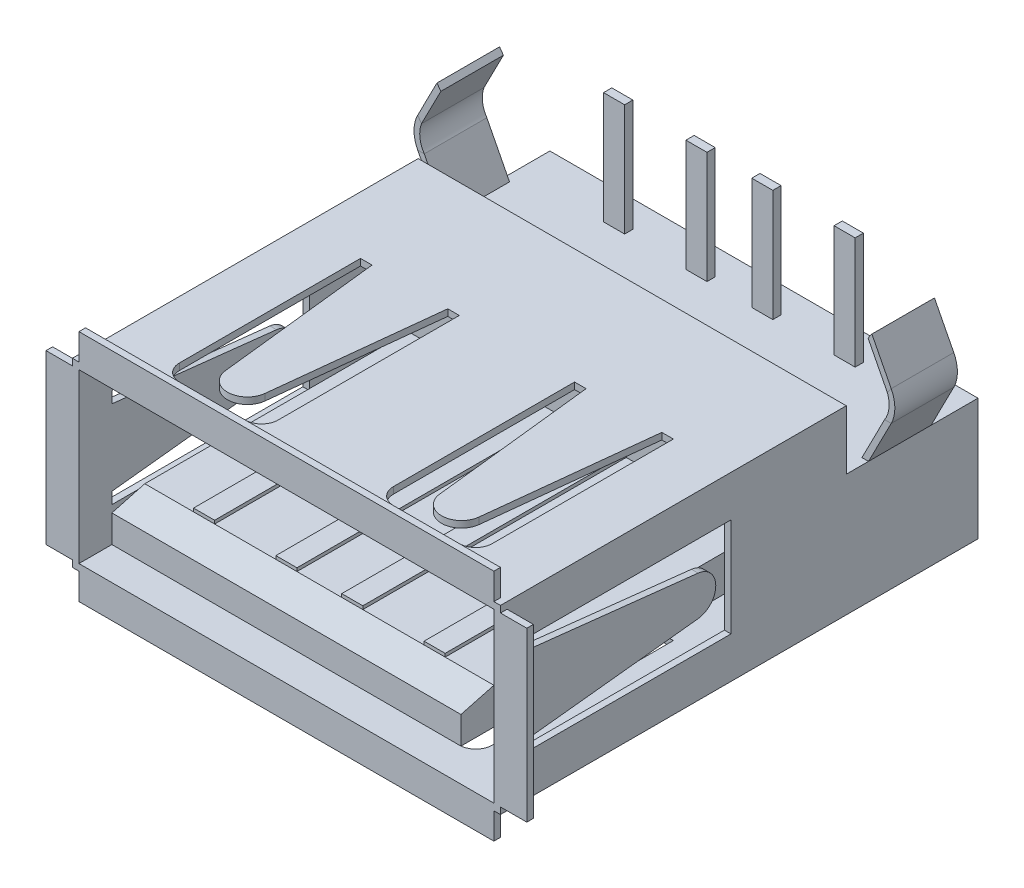
SolidWorks part; units mm, degrees
ref_plane "前视基准面" through (0, 0, 0) normal (0, 0, 1) x (1, 0, 0)
ref_plane "上视基准面" through (0, 0, 0) normal (0, 1, 0) x (1, 0, 0)
ref_plane "右视基准面" through (0, 0, 0) normal (1, 0, 0) x (0, 0, -1)
sketch "草图1" plane through (0, 0, 0) normal (0, 0, 1) x (1, 0, 0)
  line L1 (6.5, -2.75) -> (-6.5, -2.75)
  line L2 (6.5, -2.75) -> (6.5, 2.75)
  line L3 (6.5, 2.75) -> (-6.5, 2.75)
  line L4 (-6.5, -2.75) -> (-6.5, 2.75)
  line L5 (6.5, -2.75) -> (-6.5, 2.75) construction
  line L6 (6.5, 2.75) -> (-6.5, -2.75) construction
  point P0 (0, 0)
  dimension "D1" = 13
  dimension "D2" = 5.5
extrude "凸台-拉伸1" add sketch "草图1" along normal blind 14.5
sketch "草图2" plane through (0, 0, 14.5) normal (0, 0, 1) x (1, 0, 0)
  line L17 (6.3, 2.55) -> (-6.3, 2.55)
  line L18 (6.3, -2.55) -> (6.3, 2.55)
  line L19 (-6.3, -2.55) -> (6.3, -2.55)
  line L20 (-6.3, 2.55) -> (-6.3, -2.55)
  line L21 (6.3, 2.55) -> (-6.3, 2.55)
  line L22 (6.3, -2.55) -> (6.3, 2.55)
  line L23 (-6.3, -2.55) -> (6.3, -2.55)
  line L24 (-6.3, 2.55) -> (-6.3, -2.55)
  dimension "D2" = 0.2
extrude "切除-拉伸1" cut sketch "草图2" against normal blind 9
sketch "草图11" plane through (0, -2.75, 0) normal (0, -1, 0) x (1, 0, 0)
  line L0 (4.75, 7.5) -> (4.75, 13)
  line L1 (4.25, 13.5) -> (2.25, 13.5)
  line L2 (1.75, 13) -> (1.75, 7.5)
  line L3 (4.75, 7.5) -> (4.4, 7.5)
  line L4 (2.1, 7.5) -> (2.65, 12.5)
  line L5 (2.1, 7.5) -> (1.75, 7.5)
  line L6 (3.85, 12.5) -> (4.4, 7.5)
  line L7 (0, 0) -> (0, 15.6851) construction
  line L8 (3.25, 5.9079) -> (3.25, 13.4637) construction
  line L10 (6.5, 14.5) -> (6.5, 0) construction
  line L11 (-3.85, 12.5) -> (-4.4, 7.5)
  line L12 (-2.1, 7.5) -> (-1.75, 7.5)
  line L13 (-2.1, 7.5) -> (-2.65, 12.5)
  line L14 (-4.75, 7.5) -> (-4.4, 7.5)
  line L15 (-1.75, 13) -> (-1.75, 7.5)
  line L16 (-4.25, 13.5) -> (-2.25, 13.5)
  line L17 (-4.75, 7.5) -> (-4.75, 13)
  line L18 (-6.5, 14.5) -> (6.5, 14.5) construction
  arc A0 (1.75, 13) -> (2.25, 13.5) centre (2.25, 13) cw
  arc A1 (4.25, 13.5) -> (4.75, 13) centre (4.25, 13) cw
  arc A2 (2.65, 12.5) -> (3.85, 12.5) centre (3.25, 12.434) cw
  arc A3 (-2.65, 12.5) -> (-3.85, 12.5) centre (-3.25, 12.434) ccw
  arc A4 (-4.25, 13.5) -> (-4.75, 13) centre (-4.25, 13) ccw
  arc A5 (-1.75, 13) -> (-2.25, 13.5) centre (-2.25, 13) ccw
  point P17 (1.75, 13.5)
  point P20 (4.75, 13.5)
  point P35 (-4.75, 13.5)
  point P36 (-1.75, 13.5)
  dimension "D6" = 0.5
  dimension "D1" = 2.3
  dimension "D2" = 3
  dimension "D3" = 6
  dimension "D4" = 1.2
  dimension "D5" = 5
  dimension "D7" = 1
extrude "切除-拉伸3" cut sketch "草图11" against normal through all
sketch "草图12" plane through (6.5, 0, 0) normal (1, 0, 0) x (0, 0, -1)
  line L0 (-13.5, -1.5) -> (-7.5, -1.5)
  line L1 (-7.5, -1.5) -> (-7.5, 1.5)
  line L2 (-7.5, 1.5) -> (-13.5, 1.5)
  line L3 (-13.5, 1.5) -> (-13.5, 1.15)
  line L4 (-13.5, 1.15) -> (-8.5, 0.6)
  line L6 (-8.5, -0.6) -> (-13.5, -1.15)
  line L7 (-13.5, -1.15) -> (-13.5, -1.5)
  line L8 (0, 0) -> (-16.0107, 0) construction
  line L9 (-14.5, -2.75) -> (-14.5, 2.75) construction
  arc A0 (-8.5, -0.6) -> (-8.5, 0.6) centre (-8.566, 0) ccw
  dimension "D1" = 1
  dimension "D2" = 6
  dimension "D3" = 5
  dimension "D4" = 3
  dimension "D5" = 2.3
  dimension "D6" = 1.2
extrude "切除-拉伸4" cut sketch "草图12" against normal through all
sketch "草图5" plane through (0, 0, 5.5) normal (0, 0, 1) x (1, 0, 0)
  line L0 (0, -1.4303) -> (0, 3.5568) construction
  line L1 (5.3, -1.55) -> (-5.3, -1.55)
  line L2 (5.3, -1.55) -> (5.3, -0.45)
  line L3 (5.3, -0.45) -> (-5.3, -0.45)
  line L4 (-5.3, -1.55) -> (-5.3, -0.45)
  line L5 (5.3, -1.55) -> (-5.3, -0.45) construction
  line L6 (5.3, -0.45) -> (-5.3, -1.55) construction
  line L7 (-6.3, 2.55) -> (-6.3, -2.55) construction
  line L8 (-6.3, -2.55) -> (6.3, -2.55) construction
  point P0 (0, -1)
  dimension "D1" = 1.1
  dimension "D2" = 1
  dimension "D3" = 1
extrude "凸台-拉伸3" add sketch "草图5" along normal up to surface (9 mm away) up to face at (0, 0, 14.5)
chamfer "倒角1" distance 1 angle 15 1 edges at (0, -0.45, 14.5)
sketch "草图3" plane through (0, 2.75, 0) normal (0, 1, 0) x (1, 0, 0)
  line L0 (-6.5, -14.5) -> (-6.5, 0) construction
  line L1 (6.5, 0) -> (-6.5, 0)
  line L2 (6.5, 0) -> (6.5, -4)
  line L3 (6.5, -4) -> (-6.5, -4)
  line L4 (-6.5, 0) -> (-6.5, -4)
  dimension "D1" = 4
extrude "切除-拉伸2" cut sketch "草图3" against normal blind 1.8
sketch "草图9" plane through (0, 0.95, 2.45) normal (0, -1, 0) x (-1, 0, 0)
  line L0 (0, 2.45) -> (0, -1.3538) construction
  line L1 (-3.82, 1.65) -> (-3.18, 1.65)
  line L2 (-3.82, 1.65) -> (-3.82, 1.4)
  line L3 (-3.82, 1.4) -> (-3.18, 1.4)
  line L4 (-3.18, 1.65) -> (-3.18, 1.4)
  line L6 (-6.5, 2.45) -> (6.5, 2.45) construction
  line L7 (0.68, 1.4) -> (0.68, 1.65)
  line L8 (-1.32, 1.4) -> (-0.68, 1.4)
  line L9 (-1.32, 1.4) -> (-1.32, 1.65)
  line L10 (-1.32, 1.65) -> (-0.68, 1.65)
  line L11 (-0.68, 1.4) -> (-0.68, 1.65)
  line L12 (1.32, 1.65) -> (0.68, 1.65)
  line L13 (1.32, 1.4) -> (1.32, 1.65)
  line L14 (1.32, 1.4) -> (0.68, 1.4)
  line L15 (3.18, 1.65) -> (3.18, 1.4)
  line L16 (3.82, 1.4) -> (3.18, 1.4)
  line L17 (3.82, 1.65) -> (3.82, 1.4)
  line L18 (3.82, 1.65) -> (3.18, 1.65)
  line L20 (-6.5, -1.55) -> (-6.5, 2.45) construction
  line L21 (-6.5, -0.875) -> (-6.3, -0.875) construction
  line L22 (-6.5, -0.875) -> (-6.5, 1.025) construction
  line L23 (-6.5, 1.025) -> (-6.3, 1.025) construction
  line L24 (-6.3, -0.875) -> (-6.3, 1.025) construction
  point P6 (-1, 1.65)
  point P10 (-3.5, 1.65)
  point P28 (-3.82, 1.525)
  point P29 (-6.3, 0.075)
  dimension "D1" = 0.64
  dimension "D2" = 0.25
  dimension "D3" = 3.5
  dimension "D4" = 1
  dimension "D5" = 0.8
  dimension "D6" = 0.2
  dimension "D7" = 1.9
  dimension "D8" = 1.45
extrude "凸台-拉伸5" add sketch "草图9" against normal blind 3.4
sketch "草图14" plane through (0, -0.45, 0) normal (0, 1, 0) x (1, 0, 0)
  line L1 (-3.82, -5.37) -> (-3.18, -5.37)
  line L2 (-3.82, -5.37) -> (-3.82, -13.5)
  line L3 (-3.82, -13.5) -> (-3.18, -13.5)
  line L4 (-3.18, -5.37) -> (-3.18, -13.5)
  line L5 (-1.32, -5.37) -> (-0.68, -5.37)
  line L6 (-1.32, -5.37) -> (-1.32, -13.5)
  line L7 (-1.32, -13.5) -> (-0.68, -13.5)
  line L8 (-0.68, -5.37) -> (-0.68, -13.5)
  line L9 (0.68, -5.37) -> (1.32, -5.37)
  line L10 (0.68, -5.37) -> (0.68, -13.5)
  line L11 (0.68, -13.5) -> (1.32, -13.5)
  line L12 (1.32, -5.37) -> (1.32, -13.5)
  line L13 (3.18, -5.37) -> (3.82, -5.37)
  line L14 (3.18, -5.37) -> (3.18, -13.5)
  line L15 (3.18, -13.5) -> (3.82, -13.5)
  line L16 (3.82, -5.37) -> (3.82, -13.5)
  line L19 (3.18, -1.05) -> (3.18, -0.8) construction
  line L20 (3.82, -0.8) -> (3.82, -1.05) construction
  line L21 (-5.3, -13.5) -> (5.3, -13.5) construction
extrude "凸台-拉伸6" add sketch "草图14" along normal blind 0.1
sketch "草图15" plane through (0, 0.95, 0) normal (0, 1, 0) x (1, 0, 0)
  line L0 (0, 0) -> (0, -3.8038) construction
  line L5 (-6.3, -3.325) -> (-6.3, -1.425)
  line L6 (-6.5, -1.425) -> (-6.3, -1.425)
  line L7 (-6.5, -3.325) -> (-6.5, -1.425)
  line L8 (-6.5, -3.325) -> (-6.3, -3.325)
sketch "草图16" plane through (0, 0, 0) normal (0, 0, -1) x (-1, 0, 0)
  line L0 (6.5, 0.95) -> (7.1896, 2.2933)
  line L1 (7.1896, 3.2067) -> (6.6027, 4.35)
  line L3 (6.5, 0.95) -> (-6.5, 0.95) construction
  line L5 (6.5, 2.75) -> (-6.5, 2.75) construction
  arc A0 (7.1896, 2.2933) -> (7.1896, 3.2067) centre (6.3, 2.75) ccw
  point P13 (7.4241, 2.75)
  point P14 (7.3, 2.75)
  dimension "D3" = 1
  dimension "D1" = 3.4
  dimension "D2" = 7.3
sweep "扫描1" add profiles "草图15" path "草图16"
mirror "镜向1" about plane through (0, 0, 0) normal (1, 0, 0) of "扫描1"
sketch "草图17" plane through (0, 0, 14.5) normal (0, 0, 1) x (1, 0, 0)
  line L0 (-6.5, -2.75) -> (6.5, -2.75) construction
  line L1 (6.3, -2.75) -> (-6.3, -2.75)
  line L2 (6.3, -3.55) -> (6.3, -2.75)
  line L3 (6.3, -3.55) -> (-6.3, -3.55)
  line L4 (7.3, -2.55) -> (6.5, -2.55)
  line L5 (-6.5, 2.75) -> (-6.5, -2.75) construction
  line L6 (-6.5, -2.55) -> (-7.3, -2.55)
  line L7 (-6.5, -2.55) -> (-6.5, 2.55)
  line L8 (-6.3, -3.55) -> (-6.3, -2.75)
  line L9 (-7.3, -2.55) -> (-7.3, 2.55)
  line L10 (6.5, 2.75) -> (-6.5, 2.75) construction
  line L11 (6.3, 2.75) -> (-6.3, 2.75)
  line L12 (-6.5, 2.55) -> (-7.3, 2.55)
  line L13 (6.3, 3.55) -> (-6.3, 3.55)
  line L14 (-6.3, 2.75) -> (-6.3, 3.55)
  line L15 (6.5, -2.75) -> (6.5, 2.75) construction
  line L16 (6.3, 2.75) -> (6.3, 3.55)
  line L17 (6.5, -2.55) -> (6.5, 2.55)
  line L18 (6.5, 2.55) -> (7.3, 2.55)
  line L19 (7.3, -2.55) -> (7.3, 2.55)
  dimension "D1" = 14.6
  dimension "D2" = 7.1
extrude "卷边-外径14*7.1" add sketch "草图17" against normal blind 0.2
